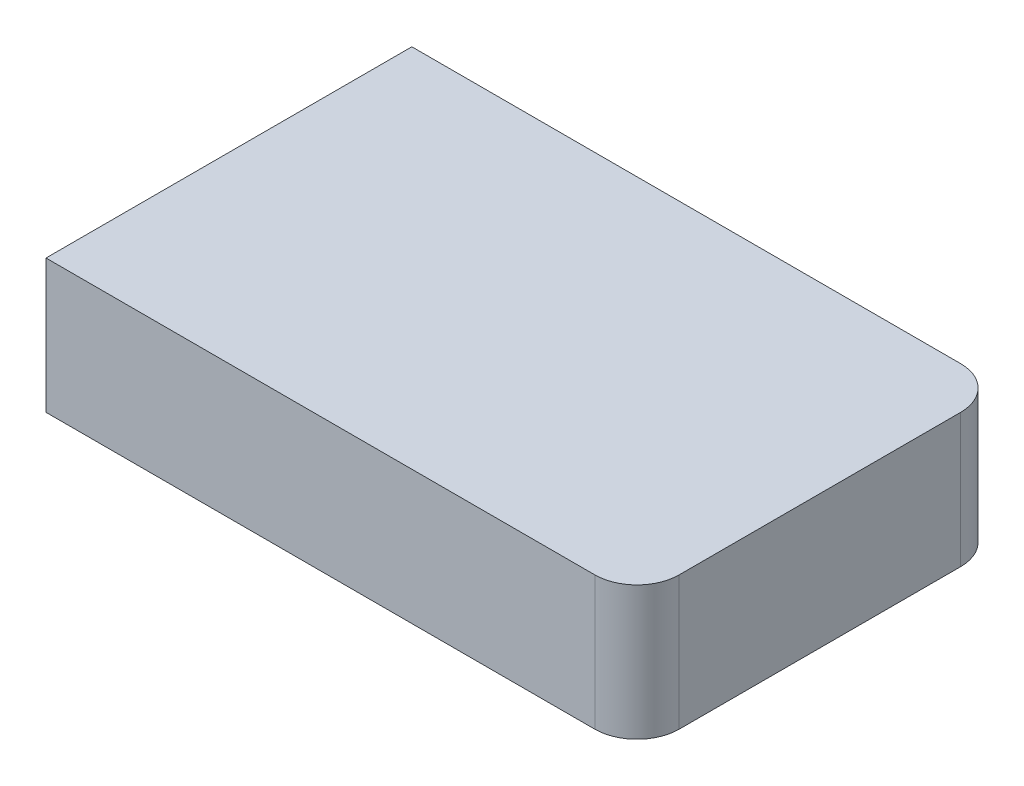
SolidWorks part; units mm, degrees
ref_plane "前视基准面" through (0, 0, 0) normal (0, 0, 1) x (1, 0, 0)
ref_plane "上视基准面" through (0, 0, 0) normal (0, 1, 0) x (1, 0, 0)
ref_plane "右视基准面" through (0, 0, 0) normal (1, 0, 0) x (0, 0, -1)
sketch "草图1" plane through (0, 0, 0) normal (0, 1, 0) x (1, 0, 0)
  line L1 (-21, 13) -> (21, 13)
  line L2 (-21, 13) -> (-21, -13)
  line L3 (-21, -13) -> (21, -13)
  line L4 (21, 13) -> (21, -13)
  line L5 (-21, 13) -> (21, -13) construction
  line L6 (-21, -13) -> (21, 13) construction
  point P0 (0, 0)
  dimension "D1" = 42
  dimension "D2" = 26
extrude "凸台-拉伸1" add sketch "草图1" along normal blind 9.5
fillet "圆角1" radius 3 2 edges at (21, 4.75, -13) (21, 4.75, 13)
